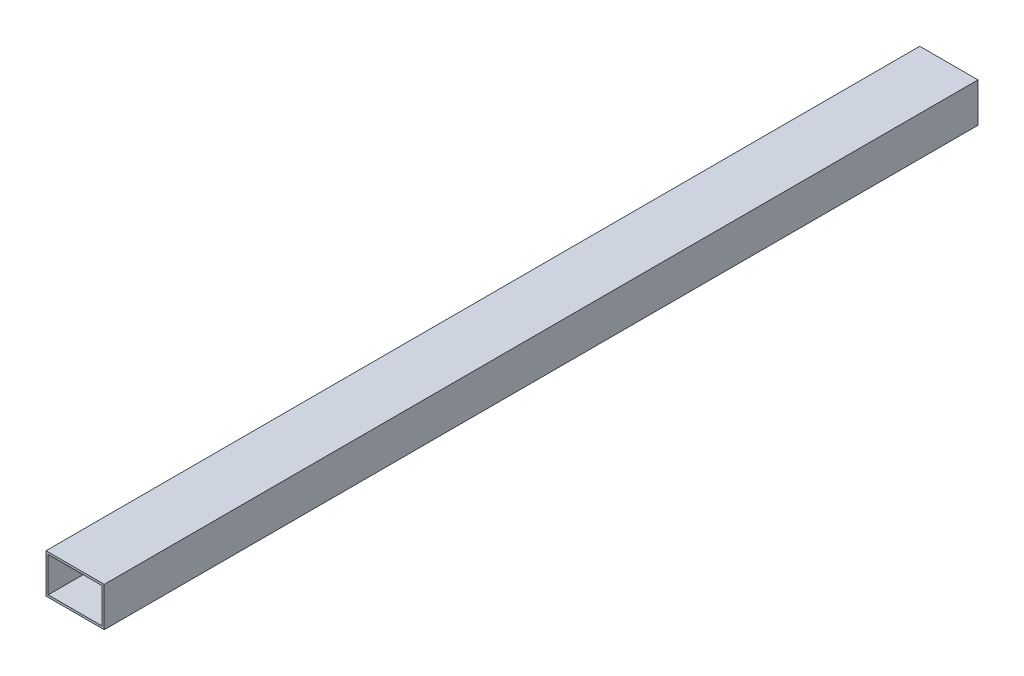
SolidWorks part; units mm, degrees
material "AISI 1045 Acier étiré à froid"
ref_plane "Plan de face" through (0, 0, 0) normal (0, 0, 1) x (1, 0, 0)
ref_plane "Plan de dessus" through (0, 0, 0) normal (0, 1, 0) x (1, 0, 0)
ref_plane "Plan de droite" through (0, 0, 0) normal (1, 0, 0) x (0, 0, -1)
sketch "Esquisse1" plane through (0, 0, 0) normal (0, 0, 1) x (1, 0, 0)
  line L1 (0, 0) -> (40, 0)
  line L2 (0, 0) -> (0, 27)
  line L3 (0, 27) -> (40, 27)
  line L4 (40, 0) -> (40, 27)
  line L5 (1.5, 25.5) -> (38.5, 25.5)
  line L6 (1.5, 25.5) -> (1.5, 1.5)
  line L7 (1.5, 1.5) -> (38.5, 1.5)
  line L8 (38.5, 25.5) -> (38.5, 1.5)
  dimension "D1" = 40
  dimension "D2" = 27
  dimension "D3" = 1.5
  dimension "D4" = 1.5
  dimension "D5" = 1.5
  dimension "D6" = 1.5
extrude "Boss.-Extru.1" add sketch "Esquisse1" along normal blind 600
sketch "Esquisse2" plane through (0, 0, 0) normal (0, 1, 0) x (1, 0, 0)
  line L0 (0, -600) -> (40, -560)
  line L1 (40, -600) -> (40, 0) construction
  line L2 (0, -600) -> (40, -600)
  line L3 (40, -600) -> (40, -560)
  dimension "D1" = 45
extrude "Enlèv. mat.-Extru.1" [suppressed] cut sketch "Esquisse2" along normal through all
sketch "Esquisse4" plane through (0, 0, 0) normal (0, 1, 0) x (1, 0, 0)
  line L0 (0, 0) -> (40, -40)
  line L1 (40, -600) -> (40, 0) construction
  line L2 (40, -40) -> (40, 0)
  line L3 (40, 0) -> (0, 0)
  dimension "D1" = 45
extrude "Enlèv. mat.-Extru.3" [suppressed] cut sketch "Esquisse4" along normal through all
